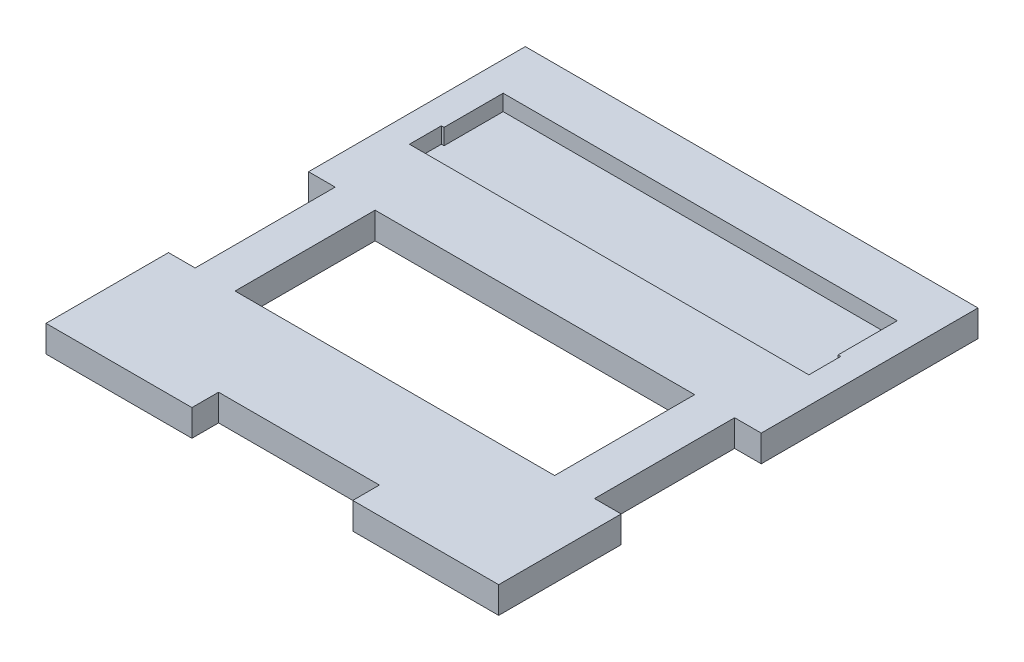
SolidWorks part; units mm, degrees
ref_plane "Front Plane" through (0, 0, 0) normal (0, 0, 1) x (1, 0, 0)
ref_plane "Top Plane" through (0, 0, 0) normal (0, 1, 0) x (1, 0, 0)
ref_plane "Right Plane" through (0, 0, 0) normal (1, 0, 0) x (0, 0, -1)
sketch "Sketch1" plane through (0, 0, 0) normal (0, 1, 0) x (1, 0, 0)
  line L1 (-42.5, -45) -> (42.5, -45)
  line L2 (-42.5, -45) -> (-42.5, 45)
  line L3 (-42.5, 45) -> (42.5, 45)
  line L4 (42.5, -45) -> (42.5, 45)
  line L5 (-42.5, -45) -> (42.5, 45) construction
  line L6 (-42.5, 45) -> (42.5, -45) construction
  point P0 (0, 0)
  dimension "D1" = 85
  dimension "D2" = 90
extrude "Boss-Extrude1" add sketch "Sketch1" along normal blind 5
sketch "Sketch2" plane through (0, 5, 0) normal (0, 1, 0) x (1, 0, 0)
  line L0 (0, -2.75) -> (0, 2.75) construction
  line L1 (-30, -22) -> (30, -22)
  line L2 (-30, -22) -> (-30, 4.3)
  line L3 (-30, 4.3) -> (30, 4.3)
  line L4 (30, -22) -> (30, 4.3)
  line L5 (-30, -22) -> (30, 4.3) construction
  line L6 (-30, 4.3) -> (30, -22) construction
  line L7 (-42.5, -45) -> (42.5, -45) construction
  line L13 (-39, 18.3) -> (39, 40.55) construction
  line L14 (-37, 39.9795) -> (39, 18.3) construction
  point P0 (0, -8.85)
  point P9 (0, 29.425)
  dimension "D1" = 60
  dimension "D2" = 23
  dimension "D3" = 26.3
  dimension "D5" = 22.25
  dimension "D6" = 78
extrude "Cut-Extrude2" cut sketch "Sketch2" against normal blind 7.5
sketch "Sketch4" plane through (0, 5, 0) normal (0, 1, 0) x (1, 0, 0)
  line L0 (-37.5, -22) -> (-42.5, -22)
  line L1 (-42.5, 45) -> (-42.5, -45) construction
  line L2 (-42.5, -22) -> (-42.5, 4.3)
  line L3 (-42.5, 4.3) -> (-37.5, 4.3)
  line L4 (-37.5, 4.3) -> (-37.5, -22)
  line L5 (0, -2.75) -> (0, 2.75) construction
  line L6 (37.5, 4.3) -> (37.5, -22)
  line L7 (42.5, 4.3) -> (37.5, 4.3)
  line L8 (42.5, -22) -> (42.5, 4.3)
  line L9 (37.5, -22) -> (42.5, -22)
  dimension "D1" = 5
  dimension "D2" = 26.3
extrude "Cut-Extrude3" cut sketch "Sketch4" against normal blind 7.5
sketch "Sketch5" plane through (0, 5, 0) normal (0, 1, 0) x (1, 0, 0)
  line L0 (0, -2.75) -> (0, 2.75) construction
  line L1 (-15.1, -40) -> (15.1, -40)
  line L2 (-15.1, -40) -> (-15.1, -45)
  line L3 (-15.1, -45) -> (15.1, -45)
  line L4 (15.1, -40) -> (15.1, -45)
  line L5 (-15.1, -40) -> (15.1, -45) construction
  line L6 (-15.1, -45) -> (15.1, -40) construction
  line L7 (-42.5, -45) -> (42.5, -45) construction
  point P0 (0, -42.5)
  dimension "D1" = 5
  dimension "D2" = 30.2
extrude "Cut-Extrude4" cut sketch "Sketch5" against normal blind 5
sketch "Sketch6" plane through (0, 5, 0) normal (0, 1, 0) x (1, 0, 0)
  line L0 (0, -2.75) -> (0, 2.75) construction
  line L1 (-37, 35.34) -> (37, 35.34)
  line L2 (-37.5, 24.24) -> (-37.5, 18.24)
  line L3 (-37.5, 18.24) -> (37.5, 18.24)
  line L4 (37.5, 24.24) -> (37.5, 18.24)
  line L5 (-37, 40.3417) -> (37.5, 18.24) construction
  line L6 (-37.5, 18.24) -> (37, 40.3417) construction
  line L7 (30, 4.3) -> (-30, 4.3) construction
  line L8 (37.5, 24.24) -> (37, 24.24)
  line L11 (-37.5, 24.24) -> (-37, 24.24)
  line L12 (-37, 35.34) -> (-37, 24.24)
  line L13 (37, 35.34) -> (37, 24.24)
  point P0 (0, 29.365)
  dimension "D1" = 75
  dimension "D2" = 6
  dimension "D3" = 13.94
  dimension "D4" = 0.5
  dimension "D5" = 11.1
extrude "Cut-Extrude5" cut sketch "Sketch6" against normal blind 3
